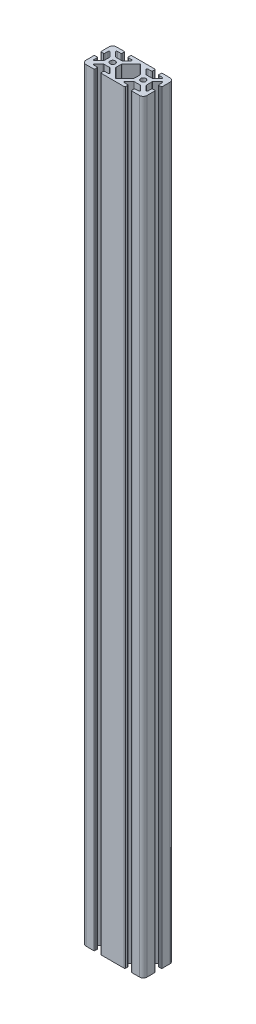
SolidWorks part; units mm, degrees
material "4032-T6"
ref_plane "Front Plane" through (0, 0, 0) normal (0, 0, 1) x (1, 0, 0)
ref_plane "Top Plane" through (0, 0, 0) normal (0, 1, 0) x (1, 0, 0)
ref_plane "Right Plane" through (0, 0, 0) normal (1, 0, 0) x (0, 0, -1)
sketch "Sketch1" plane through (0, 0, 0) normal (0, 1, 0) x (1, 0, 0)
  line L1 (5, 0) -> (75, 0)
  line L2 (0, -5) -> (0, -35)
  line L3 (5, -40) -> (75, -40)
  line L4 (80, -5) -> (80, -35)
  arc A0 (75, -40) -> (80, -35) centre (75, -35) ccw
  arc A1 (80, -5) -> (75, 0) centre (75, -5) ccw
  arc A2 (5, -40) -> (0, -35) centre (5, -35) cw
  arc A3 (0, -5) -> (5, 0) centre (5, -5) cw
  point P7 (80, -40)
  point P10 (80, 0)
  point P15 (0, 0)
  dimension "D3" = 5
  dimension "D1" = 80
  dimension "D2" = 40
extrude "Boss-Extrude1" add sketch "Sketch1" along normal blind 1000 contours L3 A0 L4 A1 L1 A3 L2 A2
sketch "Sketch3" plane through (0, 1000, 0) normal (0, 1, 0) x (1, 0, 0)
  line L0 (40, -2.5254) -> (40, -32.3671)
  line L1 (0, -5) -> (0, -35) construction
  line L2 (5, 0) -> (75, 0) construction
  circle A0 centre (20, -20) radius 3.4
  dimension "D4" = 6.8
  dimension "D1" = 40
  dimension "D2" = 20
  dimension "D3" = 20
extrude "Cut-Extrude1" cut sketch "Sketch3" against normal blind 1000 contours A0
ref_plane "mirro-plane" through (40, 0, 0) normal (1, 0, 0) x (0, 0, -1)
mirror "Mirror3" about plane through (40, 0, 0) normal (1, 0, 0) of "Cut-Extrude1"
ref_plane "sk5mirrorPlane" through (0, 0, 20) normal (0, 0, 1) x (1, 0, 0)
sketch "Sketch7" plane through (0, 0, 0) normal (0, -1, 0) x (-1, 0, 0)
  line L2 (-5, -40) -> (-75, -40) construction
  line L4 (-15.9, -40) -> (-24.1, -40)
  line L8 (-15.9, -40) -> (-15.9, -36.5)
  line L12 (-16.3092, -27.8) -> (-23.6908, -27.8)
  line L23 (-10.5103, -35.5) -> (-14.9, -35.5)
  line L25 (-24.1, -40) -> (-24.1, -36.5)
  line L27 (-15.6082, -28.0868) -> (-9.8093, -33.7868)
  line L31 (-29.4898, -35.5) -> (-25.1, -35.5)
  line L43 (-24.3918, -28.0868) -> (-30.1908, -33.7868)
  arc A0 (-24.3918, -28.0868) -> (-23.6908, -27.8) centre (-23.6908, -28.8) cw
  arc A1 (-16.3092, -27.8) -> (-15.6082, -28.0868) centre (-16.3092, -28.8) cw
  arc A2 (-30.1908, -33.7868) -> (-29.4898, -35.5) centre (-29.4898, -34.5) ccw
  arc A3 (-9.8093, -33.7868) -> (-10.5103, -35.5) centre (-10.5103, -34.5) cw
  arc A4 (-25.1, -35.5) -> (-24.1, -36.5) centre (-25.1, -36.5) cw
  arc A5 (-14.9, -35.5) -> (-15.9, -36.5) centre (-14.9, -36.5) ccw
  point P96 (-24.1, -35.5)
  dimension "D17" = 0
  dimension "D18" = 1
  dimension "D8" = 12.2
extrude "Cut-Extrude2" cut sketch "Sketch7" against normal blind 1000
fillet "Fillet1" radius 1 2 edges at (15.9, 500, 40) (24.1, 500, 40)
mirror "Mirror8" about plane through (40, 0, 0) normal (1, 0, 0) of "Cut-Extrude2"
fillet "Fillet2" radius 1 1 edges at (55.9, 500, 40)
fillet "Fillet3" radius 1 1 edges at (64.1, 500, 40)
sketch "Sketch9" plane through (0, 0, 0) normal (0, 1, 0) x (1, 0, 0)
  line L1 (14.8998, -4.5007) -> (10.4505, -4.5007)
  line L3 (24.0998, -3.5) -> (24.1, 0)
  line L4 (15.8998, -3.5008) -> (15.9, 0)
  line L5 (15.9, 0) -> (24.1, 0)
  line L6 (16.1497, -12.2) -> (23.8503, -12.2)
  line L7 (5, 0) -> (75, 0) construction
  line L8 (25.0998, -4.5) -> (29.5503, -4.5)
  line L12 (9.7434, -6.2078) -> (15.4426, -11.9071)
  line L16 (24.5574, -11.9071) -> (30.2574, -6.2071)
  arc A0 (15.8998, -3.5008) -> (14.8998, -4.5007) centre (14.8998, -3.5007) cw
  arc A1 (24.0998, -3.5) -> (25.0998, -4.5) centre (25.0998, -3.5) ccw
  arc A2 (29.5503, -4.5) -> (30.2574, -6.2071) centre (29.5503, -5.5) cw
  arc A3 (24.5574, -11.9071) -> (23.8503, -12.2) centre (23.8503, -11.2) cw
  arc A4 (9.7434, -6.2078) -> (10.4505, -4.5007) centre (10.4505, -5.5007) cw
  arc A5 (15.4426, -11.9071) -> (16.1497, -12.2) centre (16.1497, -11.2) ccw
  dimension "D2" = 1
  dimension "D1" = 0
  dimension "D5" = 12.2
  dimension "D6" = 4.5
extrude "Cut-Extrude3" cut sketch "Sketch9" along normal blind 1000
mirror "Mirror9" about plane through (40, 0, 0) normal (1, 0, 0) of "Cut-Extrude3"
sketch "Sketch10" plane through (0, 0, 0) normal (0, 1, 0) x (1, 0, 0)
  line L0 (4.5, -14.9) -> (4.5, -10.5861)
  line L4 (0, -24.1) -> (3.5, -24.1)
  line L5 (0, -15.9) -> (3.5, -15.9)
  line L8 (12.2, -23.4919) -> (12.2, -16.5081)
  line L10 (0, -5) -> (0, -35) construction
  line L13 (4.5, -29.4139) -> (4.5, -25.1)
  line L25 (11.9205, -24.1853) -> (6.2205, -30.1074)
  line L26 (11.9205, -15.8147) -> (6.2205, -9.8926)
  line L29 (0, -24.1) -> (0, -15.9)
  arc A0 (4.5, -14.9) -> (3.5, -15.9) centre (3.5, -14.9) cw
  arc A1 (3.5, -24.1) -> (4.5, -25.1) centre (3.5, -25.1) cw
  arc A2 (6.2205, -9.8926) -> (4.5, -10.5861) centre (5.5, -10.5861) ccw
  arc A3 (11.9205, -15.8147) -> (12.2, -16.5081) centre (11.2, -16.5081) cw
  arc A4 (11.9205, -24.1853) -> (12.2, -23.4919) centre (11.2, -23.4919) ccw
  arc A5 (4.5, -29.4139) -> (6.2205, -30.1074) centre (5.5, -29.4139) ccw
  dimension "D3" = 1
  dimension "D7" = 12.2
  dimension "D9" = 4.5
  dimension "D17" = 0
extrude "Cut-Extrude4" cut sketch "Sketch10" along normal blind 1000
fillet "Fillet4" radius 1 1 edges at (24.1, 500, 0)
fillet "Fillet5" radius 1 1 edges at (64.1, 500, 0)
fillet "Fillet6" radius 1 1 edges at (55.9, 500, 0)
fillet "Fillet7" radius 1 1 edges at (15.9, 500, 0)
fillet "Fillet8" radius 1 1 edges at (0, 500, 24.1)
fillet "Fillet9" radius 1 1 edges at (0, 500, 15.9)
sketch "Sketch11" plane through (0, 0, 0) normal (0, 1, 0) x (1, 0, 0)
  line L0 (75.5, -29.6797) -> (75.5, -25.1)
  line L1 (80, -5) -> (80, -35) construction
  line L2 (67.5, -16.0953) -> (67.5, -23.9047)
  line L5 (75.5, -14.9) -> (75.5, -10.3203)
  line L7 (80, -24.1) -> (80, -15.9)
  line L8 (80, -5) -> (80, -35) construction
  line L13 (113.5168, -27.8) -> (113.5178, -27.6385)
  line L17 (67.8065, -15.3748) -> (73.8065, -9.5998)
  line L63 (67.8065, -24.6252) -> (73.8065, -30.4002)
  line L66 (76.5, -15.9) -> (80, -15.9)
  line L68 (76.5, -24.1) -> (80, -24.1)
  arc A44 (75.5, -25.1) -> (76.5, -24.1) centre (76.5, -25.1) cw
  arc A45 (75.5, -14.9) -> (76.5, -15.9) centre (76.5, -14.9) ccw
  arc A46 (73.8065, -9.5998) -> (75.5, -10.3203) centre (74.5, -10.3203) cw
  arc A47 (73.8065, -30.4002) -> (75.5, -29.6797) centre (74.5, -29.6797) ccw
  arc A48 (67.8065, -24.6252) -> (67.5, -23.9047) centre (68.5, -23.9047) cw
  arc A49 (67.8065, -15.3748) -> (67.5, -16.0953) centre (68.5, -16.0953) ccw
  dimension "D3" = 1
  dimension "D2" = 4.5
  dimension "D4" = 12.5
ref_plane "offset1" through (60, 0, 0) normal (1, 0, 0) x (0, 0, -1)
mirror "Mirror10" about plane through (40, 0, 0) normal (1, 0, 0) of "Cut-Extrude4"
fillet "Fillet10" radius 1 1 edges at (80, 500, 15.9)
fillet "Fillet11" radius 1 1 edges at (80, 500, 24.1)
mirror "Mirror11" about plane through (60, 0, 0) normal (1, 0, 0) of "Mirror10"
ref_plane "Plane2" through (20, 0, 0) normal (-1, 0, 0) x (0, 0, 1)
mirror "Mirror12" about plane through (20, 0, 0) normal (-1, 0, 0) of "Cut-Extrude4"
sketch "Sketch12" plane through (0, 0, 0) normal (0, -1, 0) x (-1, 0, 0)
  line L0 (-28.0795, -24.1853) -> (-39.3271, -35.8711)
  line L2 (-51.9226, -24.2109) -> (-40.7702, -35.8689)
  line L4 (-39.2795, -4.1783) -> (-28.0795, -15.8147)
  line L7 (-51.9205, -15.8147) -> (-40.7205, -4.1783)
  line L8 (-27.8, -23.4919) -> (-27.8, -16.5081)
  line L9 (-52.2, -23.5196) -> (-52.2, -16.5081)
  line L10 (-52.2, -23.4919) -> (-52.2, -16.5081) construction
  line L11 (-27.8, -23.4919) -> (-27.8, -16.5081) construction
  arc A0 (-39.2795, -4.1783) -> (-40.7205, -4.1783) centre (-40, -4.8718) ccw
  arc A1 (-39.3271, -35.8711) -> (-40.7702, -35.8689) centre (-40.0476, -35.1776) cw
  arc A2 (-51.9205, -15.8147) -> (-52.2, -16.5081) centre (-51.2, -16.5081) ccw
  arc A3 (-52.2, -23.5196) -> (-51.9226, -24.2109) centre (-51.2, -23.5196) ccw
  arc A4 (-28.0795, -15.8147) -> (-27.8, -16.5081) centre (-28.8, -16.5081) cw
  arc A5 (-27.8, -23.4919) -> (-28.0795, -24.1853) centre (-28.8, -23.4919) cw
  dimension "D3" = 1
  dimension "D4" = 1
  dimension "D1" = 0
  dimension "D2" = 0
extrude "Cut-Extrude5" cut sketch "Sketch12" against normal blind 1000
